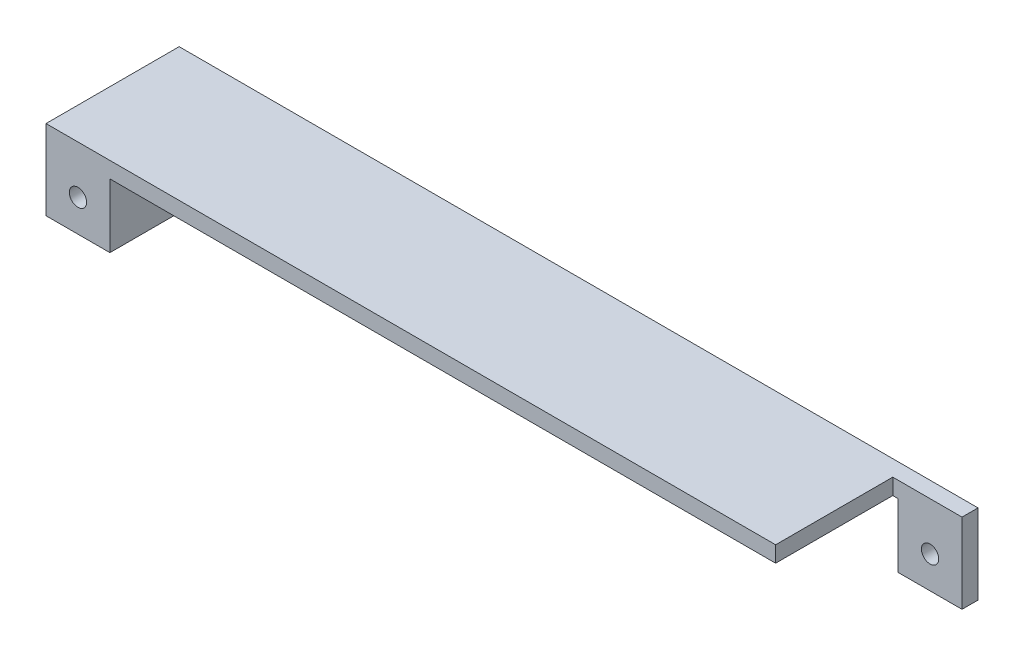
SolidWorks part; units mm, degrees
ref_plane "Front Plane" through (0, 0, 0) normal (0, 0, 1) x (1, 0, 0)
ref_plane "Top Plane" through (0, 0, 0) normal (0, 1, 0) x (1, 0, 0)
ref_plane "Right Plane" through (0, 0, 0) normal (1, 0, 0) x (0, 0, -1)
sketch "Sketch1" plane through (0, 0, 0) normal (0, 1, 0) x (1, 0, 0)
  line L1 (0, 0) -> (150, 0)
  line L2 (0, 0) -> (0, 25)
  line L3 (0, 25) -> (150, 25)
  line L4 (150, 0) -> (150, 25)
  dimension "D1" = 150
  dimension "D2" = 25
extrude "Boss-Extrude1" add sketch "Sketch1" along normal blind 3
sketch "Sketch2" plane through (0, 0, 0) normal (0, -1, 0) x (1, 0, 0)
  line L0 (75, 0) -> (75, -25) construction
  line L1 (0, 0) -> (12, 0)
  line L2 (0, 0) -> (0, -25)
  line L3 (0, -25) -> (12, -25)
  line L4 (12, 0) -> (12, -25)
  line L5 (0, 0) -> (150, 0) construction
  line L6 (150, -25) -> (0, -25) construction
  line L7 (150, -25) -> (138, -25)
  line L8 (138, 0) -> (138, -25)
  line L9 (150, 0) -> (138, 0)
  line L10 (150, 0) -> (150, -25)
  line L11 (0, -12.5) -> (150, -12.5) construction
  line L12 (0, -25) -> (0, 0) construction
  line L13 (150, 0) -> (150, -25) construction
  dimension "D1" = 25
  dimension "D2" = 12
extrude "Boss-Extrude2" add sketch "Sketch2" along normal blind 12
sketch "Sketch4" plane through (0, 0, 0) normal (0, 0, 1) x (1, 0, 0)
  line L0 (12, -12) -> (12, 0) construction
  line L1 (12, -12) -> (0, -12) construction
  line L2 (75, 3) -> (75, 0) construction
  line L3 (0, 3) -> (150, 3) construction
  line L4 (12, 0) -> (138, 0) construction
  circle A0 centre (6, -6) radius 1.625
  circle A1 centre (144, -6) radius 1.625
  dimension "D1" = 3.25
  dimension "D2" = 6
  dimension "D3" = 6
extrude "Cut-Extrude1" cut sketch "Sketch4" against normal through all
sketch "Sketch5" plane through (0, 3, 0) normal (0, 1, 0) x (1, 0, 0)
  line L0 (150, 25) -> (0, 25) construction
  line L1 (150, 0) -> (137, 0)
  line L2 (150, 0) -> (150, 22)
  line L3 (150, 22) -> (137, 22)
  line L4 (137, 0) -> (137, 22)
  dimension "D1" = 3
  dimension "D2" = 13
extrude "Cut-Extrude2" cut sketch "Sketch5" against normal through all
